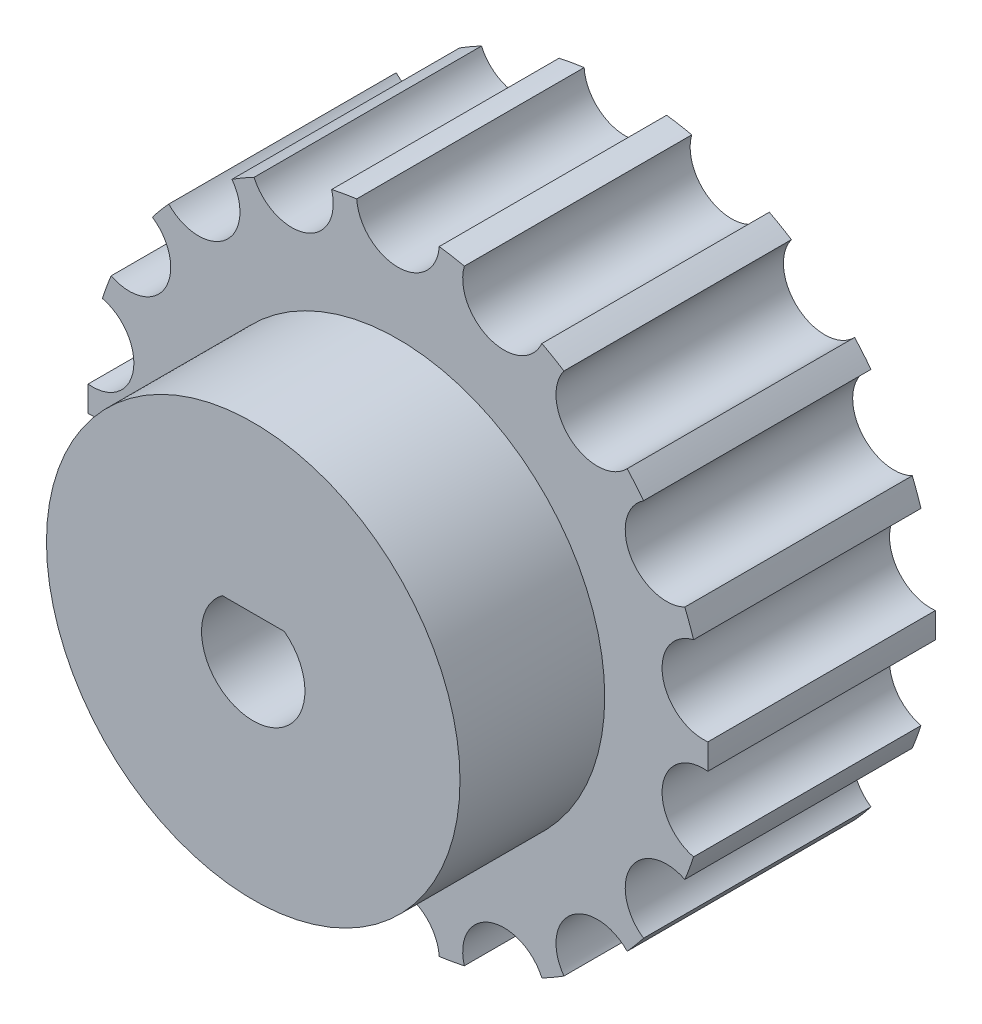
SolidWorks part; units mm, degrees
ref_plane "前视基准面" through (0, 0, 0) normal (0, 0, 1) x (1, 0, 0)
ref_plane "上视基准面" through (0, 0, 0) normal (0, 1, 0) x (1, 0, 0)
ref_plane "右视基准面" through (0, 0, 0) normal (1, 0, 0) x (0, 0, -1)
sketch "Sketch1" plane through (0, 0, 0) normal (0, 0, 1) x (1, 0, 0)
  circle A0 centre (0, 0) radius 15
  dimension "D1" = 30
extrude "Boss-Extrude1" add sketch "Sketch1" along normal blind 11
sketch "Sketch2" plane through (0, 0, 11) normal (0, 0, 1) x (1, 0, 0)
  circle A0 centre (0, 15) radius 2
  circle A1 centre (0, 0) radius 15 construction
  circle A2 centre (5.1303, 14.0954) radius 2
  circle A3 centre (9.6418, 11.4907) radius 2
  circle A4 centre (12.9904, 7.5) radius 2
  circle A5 centre (14.7721, 2.6047) radius 2
  circle A6 centre (14.7721, -2.6047) radius 2
  circle A7 centre (12.9904, -7.5) radius 2
  circle A8 centre (9.6418, -11.4907) radius 2
  circle A9 centre (5.1303, -14.0954) radius 2
  circle A10 centre (0, -15) radius 2
  circle A11 centre (-5.1303, -14.0954) radius 2
  circle A12 centre (-9.6418, -11.4907) radius 2
  circle A13 centre (-12.9904, -7.5) radius 2
  circle A14 centre (-14.7721, -2.6047) radius 2
  circle A15 centre (-14.7721, 2.6047) radius 2
  circle A16 centre (-12.9904, 7.5) radius 2
  circle A17 centre (-9.6418, 11.4907) radius 2
  circle A18 centre (-5.1303, 14.0954) radius 2
  dimension "D1" = 18
extrude "Cut-Extrude1" cut sketch "Sketch2" against normal blind 11
sketch "Sketch3" plane through (0, 0, 11) normal (0, 0, 1) x (1, 0, 0)
  circle A0 centre (0, 0) radius 2.5
  dimension "D1" = 5
extrude "Cut-Extrude2" cut sketch "Sketch3" against normal blind 11
sketch "Sketch5" plane through (0, 0, 11) normal (0, 0, 1) x (1, 0, 0)
  circle A0 centre (0, 0) radius 2.5
  circle A1 centre (0, 0) radius 10
  dimension "D1" = 20
extrude "Boss-Extrude2" add sketch "Sketch5" along normal blind 7
sketch "Sketch6" plane through (0, 0, 18) normal (0, 0, 1) x (1, 0, 0)
  line L0 (-1.5691, 2) -> (1.4281, 2) construction
  line L1 (1.5, 2) -> (-1.5, 2)
  arc A0 (1.5, 2) -> (-1.5, 2) centre (0, 0) ccw
  dimension "D1" = 2
extrude "Boss-Extrude3" add sketch "Sketch6" against normal up to surface (18 mm away) up to face at (2.5, 0, 0)
